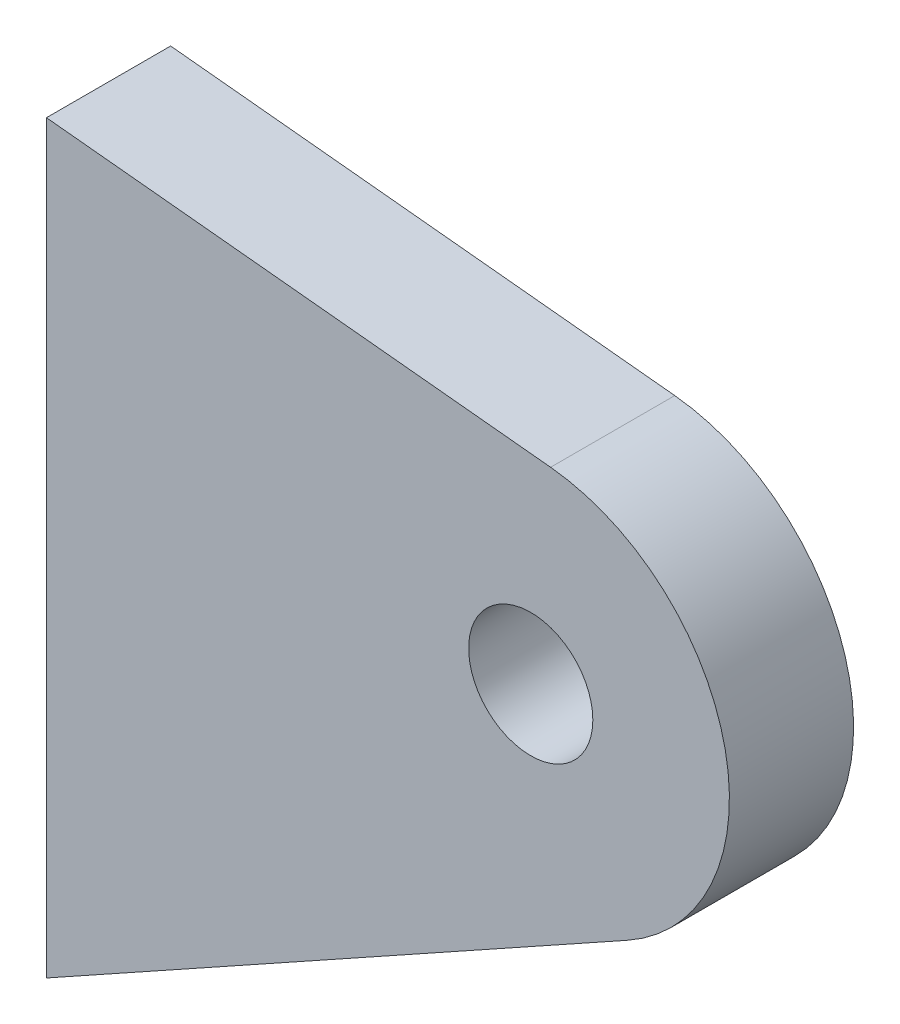
SolidWorks part; units mm, degrees
material "Alliage 1060"
ref_plane "Plan de face" through (0, 0, 0) normal (0, 0, 1) x (1, 0, 0)
ref_plane "Plan de dessus" through (0, 0, 0) normal (0, 1, 0) x (1, 0, 0)
ref_plane "Plan de droite" through (0, 0, 0) normal (1, 0, 0) x (0, 0, -1)
sketch "Esquisse1" plane through (0, 0, 0) normal (0, 0, 1) x (1, 0, 0)
  line L3 (-19.5, 10) -> (-19.5, -20)
  line L4 (0.8, 7.9599) -> (-19.5, 10)
  line L5 (-19.5, -20) -> (3.8886, -6.9914)
  line L6 (-19.5, 10) -> (-19.5, -20)
  line L7 (0.8, 7.9599) -> (-19.5, 10)
  line L8 (-19.5, -20) -> (3.8886, -6.9914)
  circle A0 centre (0, 0) radius 2.5
  arc A2 (3.8886, -6.9914) -> (0.8, 7.9599) centre (0, 0) ccw
  arc A3 (3.8886, -6.9914) -> (0.8, 7.9599) centre (0, 0) ccw
  dimension "D2" = 0
  dimension "D1" = 5
extrude "Extrusion1" add sketch "Esquisse1" along normal blind 5
hole_wizard "Trou taraudé M3x0.51" positions "Esquisse3" profile "Esquisse2" tap size "M3x0.5" standard "Ansi Métrique"
sketch "Esquisse3" plane through (-19.5, 0, 0) normal (-1, 0, 0) x (0, 0, 1)
  circle A0 centre (2.5, -16) radius 1.5 construction
  circle A1 centre (2.5, 6) radius 1.5 construction
  point P0 (2.5, 6)
  point P1 (2.5, -16)
sketch "Esquisse2" plane through (-19.5, 6, 2.5) normal (0, 1, 0) x (0, 0, 1)
  line L0 (0, 0) -> (0, 9.8511)
  line L1 (0, 9.8511) -> (1.25, 9.1)
  line L2 (1.25, 9.1) -> (1.25, 0)
  line L5 (1.25, 0) -> (0, 0)
  line L10 (0, 9.8511) -> (-1.25, 9.1) construction
  line L11 (0, -6.35) -> (0, 107.95) construction
  dimension "Diamètre du trou pour taraudage" = 2.5
  dimension "Profondeur du trou pour taraudage" = 9.1
  dimension "Angle de pointe" = 118
cosmetic thread "Filetage de perçage1" parameters "D1"=7, "D2"=3
cosmetic thread "Filetage de perçage2" parameters "D1"=7, "D2"=3
